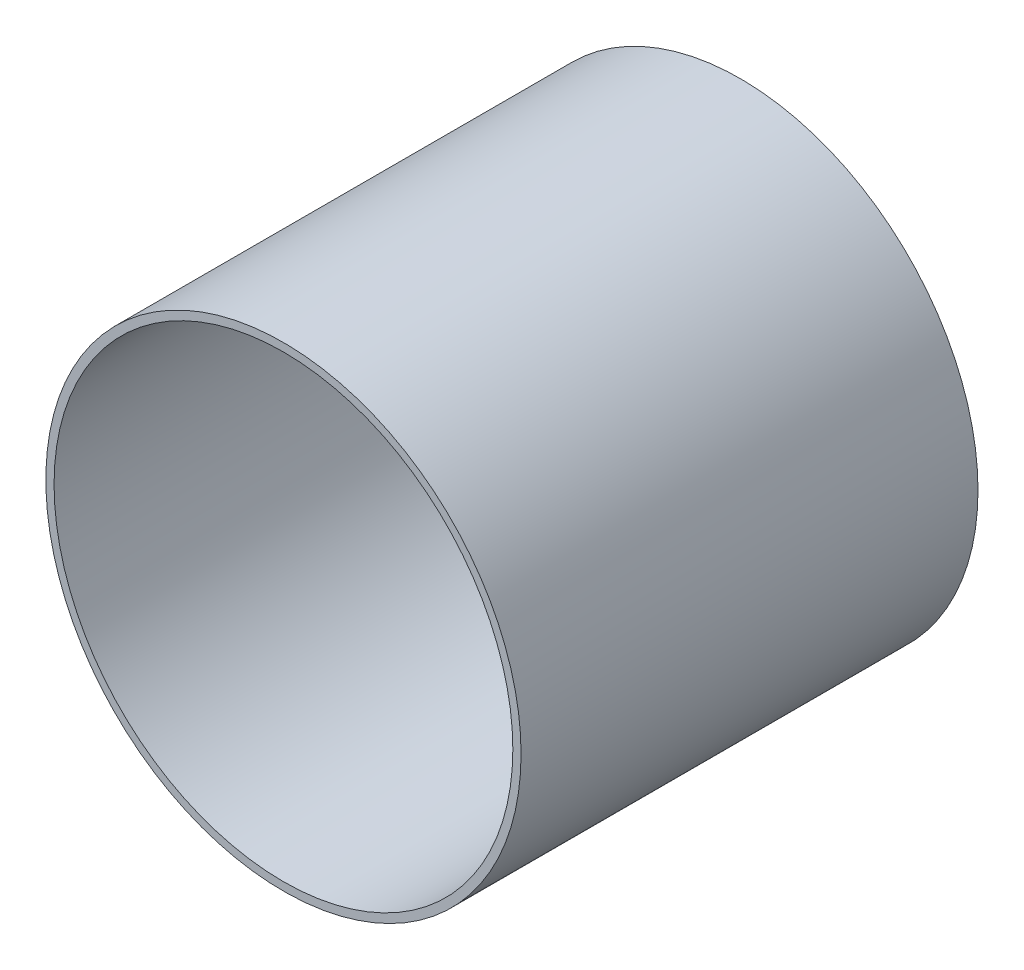
SolidWorks part; units mm, degrees
ref_plane "Front Plane" through (0, 0, 0) normal (0, 0, 1) x (1, 0, 0)
ref_plane "Top Plane" through (0, 0, 0) normal (0, 1, 0) x (1, 0, 0)
ref_plane "Right Plane" through (0, 0, 0) normal (1, 0, 0) x (0, 0, -1)
sketch "Sketch1" plane through (0, 0, 0) normal (0, 0, 1) x (1, 0, 0)
  circle A0 centre (0, 0) radius 12.55
  circle A1 centre (0, 0) radius 13
  dimension "D1" = 26
  dimension "D2" = 25.1
extrude "Boss-Extrude1" add sketch "Sketch1" along normal blind 25
